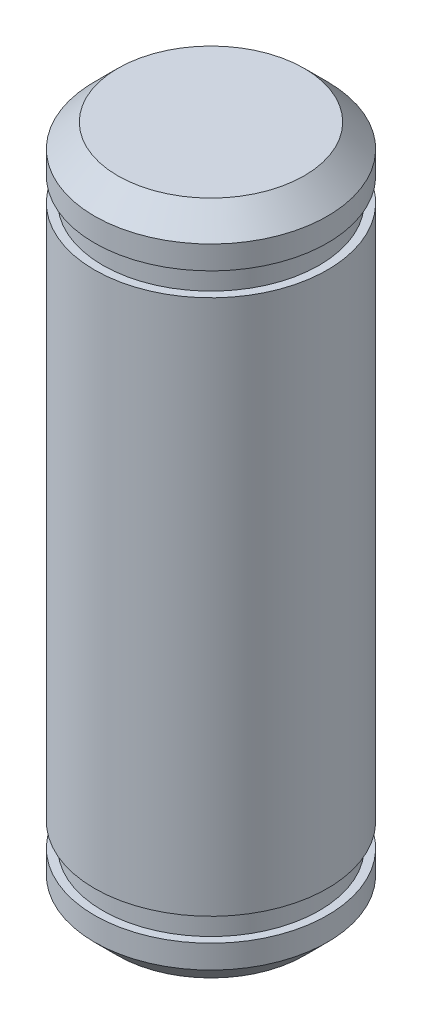
SolidWorks part; units mm, degrees
ref_plane "前视基准面" through (0, 0, 0) normal (0, 0, 1) x (1, 0, 0)
ref_plane "上视基准面" through (0, 0, 0) normal (0, 1, 0) x (1, 0, 0)
ref_plane "右视基准面" through (0, 0, 0) normal (1, 0, 0) x (0, 0, -1)
other "Configuration Table"
sketch "草图1" plane through (0, 0, 0) normal (0, 0, 1) x (1, 0, 0)
  line L0 (0, 23.0737) -> (0, -19.8109) construction
  line L1 (0, 16) -> (5, 16)
  line L2 (5, 16) -> (5, -2)
  line L4 (5, -2) -> (5, -7)
  line L6 (5, -7) -> (5, -13)
  line L7 (5, -13) -> (0, -13)
  line L8 (0, 16) -> (0, -13)
  dimension "D1" = 5
  dimension "D2" = 29
  dimension "D3" = 5
  dimension "D4" = 13
revolve "旋转1" add sketch "草图1" angle 360 about L0
chamfer "倒角1" distance 1 angle 45 2 edges at (0, -13, 5) (0, 16, 5)
ref_plane "基准面1" through (0, 1.5, 0) normal (0, 1, 0) x (1, 0, 0)
sketch "草图2" plane through (0, 16, 0) normal (0, 1, 0) x (1, 0, 0)
  circle A0 centre (0, 0) radius 4.65
  circle A1 centre (0, 0) radius 5
  dimension "D1" = 9.3
  dimension "D2" = 10
extrude "切除-拉伸1" cut sketch "草图2" against normal blind 1 from offset 2 offset against normal yes
mirror "镜向1" about plane through (0, 1.5, 0) normal (0, 1, 0) of "切除-拉伸1"
